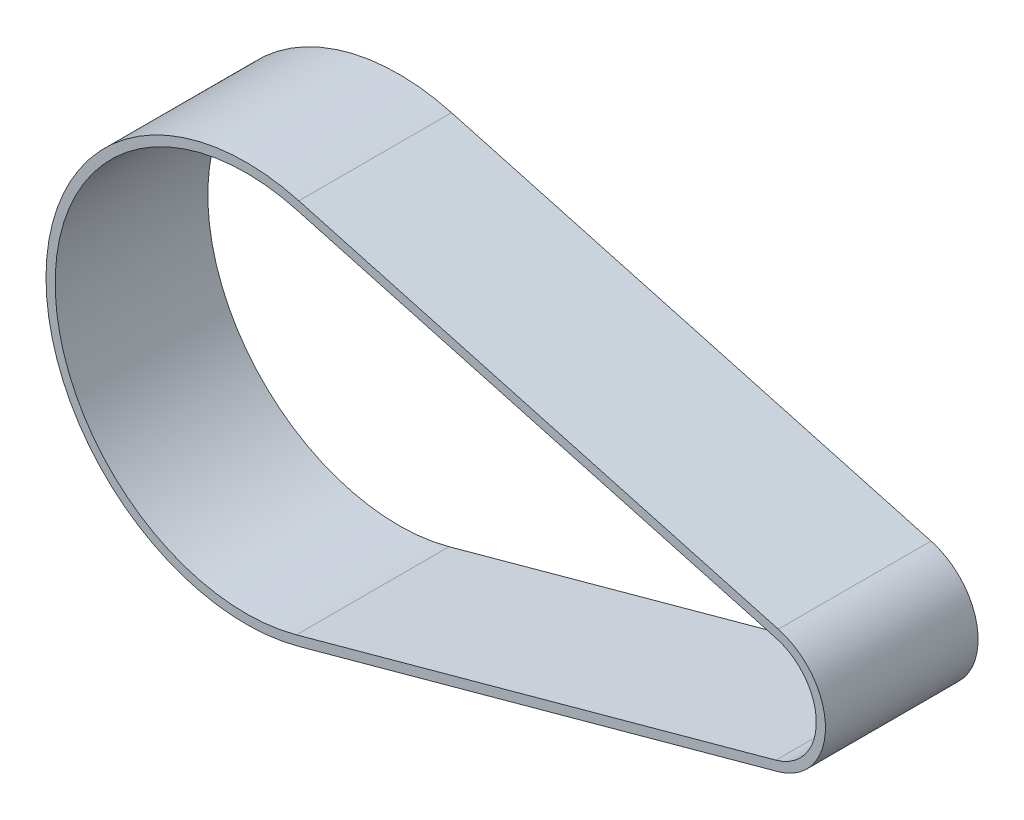
SolidWorks part; units mm, degrees
material "Rubber"
ref_plane "Front Plane" through (0, 0, 0) normal (0, 0, 1) x (1, 0, 0)
ref_plane "Top Plane" through (0, 0, 0) normal (0, 1, 0) x (1, 0, 0)
ref_plane "Right Plane" through (0, 0, 0) normal (1, 0, 0) x (0, 0, -1)
sketch "Sketch1" plane through (0, 0, 0) normal (0, 0, 1) x (1, 0, 0)
  line L0 (13.75, 0) -> (-13.75, 0) construction
  line L1 (-76.148, 30.1511) -> (2.3705, 8.6615)
  line L2 (-76.148, -30.1511) -> (2.3705, -8.6615)
  line L3 (-75.752, 31.5979) -> (2.7665, 10.1083)
  line L4 (-75.752, -31.5979) -> (2.7665, -10.1083)
  arc A0 (-76.148, 30.1511) -> (-76.148, -30.1511) centre (-84.4, 0) ccw
  arc A1 (2.3705, -8.6615) -> (2.3705, 8.6615) centre (0, 0) ccw
  arc A2 (2.7665, -10.1083) -> (2.7665, 10.1083) centre (0, 0) ccw
  arc A3 (-75.752, 31.5979) -> (-75.752, -31.5979) centre (-84.4, 0) ccw
  arc A4 (2.3705, -8.6615) -> (2.3705, 8.6615) centre (0, 0) ccw construction
  circle A5 centre (-84.4, 0) radius 34.7298 construction
  arc A6 (-90.4737, 30.6643) -> (-94.252, 29.6669) centre (-84.4, 0) ccw construction
  arc A7 (8.2209, 3.6135) -> (7.7681, 4.5052) centre (0, 0) ccw construction
  dimension "D1" = 1.5
extrude "Boss-Extrude1" add sketch "Sketch1" along normal blind 25
